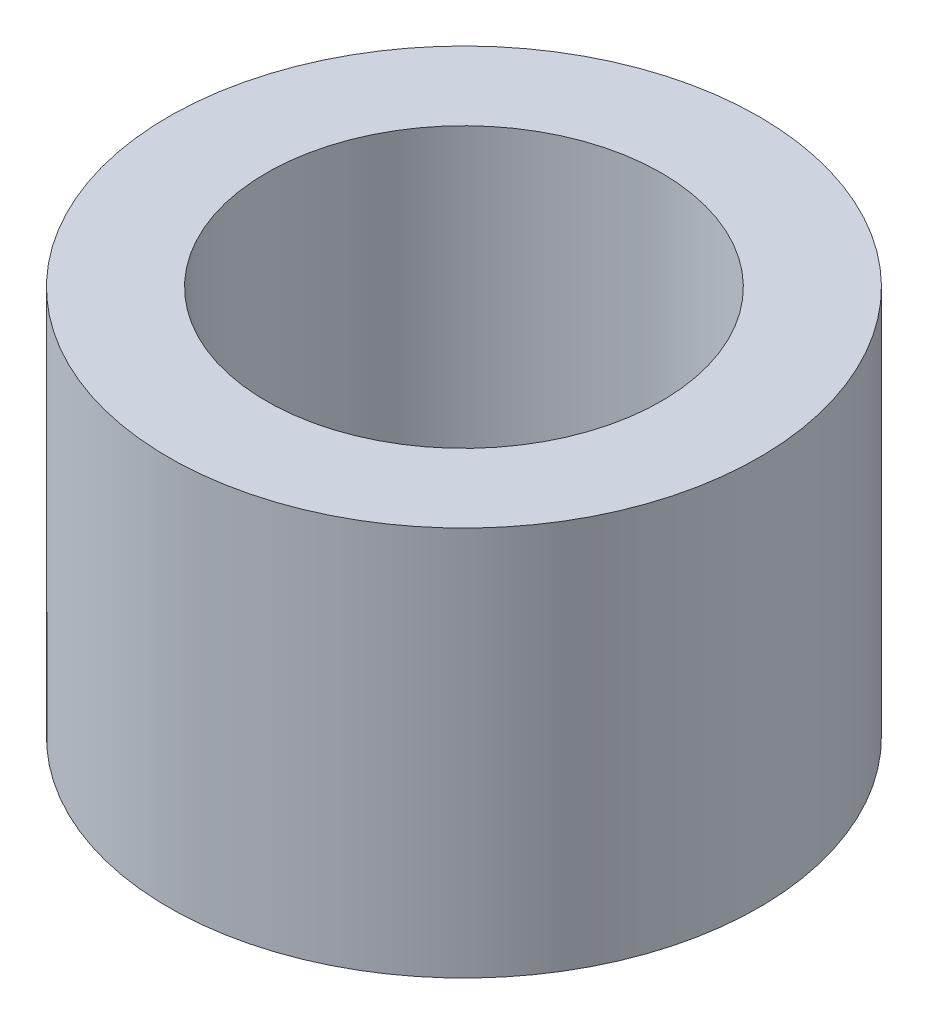
SolidWorks part; units mm, degrees
ref_plane "Front Plane" through (0, 0, 0) normal (0, 0, 1) x (1, 0, 0)
ref_plane "Top Plane" through (0, 0, 0) normal (0, 1, 0) x (1, 0, 0)
ref_plane "Right Plane" through (0, 0, 0) normal (1, 0, 0) x (0, 0, -1)
sketch "Sketch1" plane through (0, 0, 0) normal (0, 1, 0) x (1, 0, 0)
  circle A0 centre (0, 0) radius 6.35
  circle A1 centre (0, 0) radius 4.25
  dimension "D1" = 12.7
  dimension "D2" = 8.5
extrude "Boss-Extrude1" add sketch "Sketch1" along normal blind 8.382
